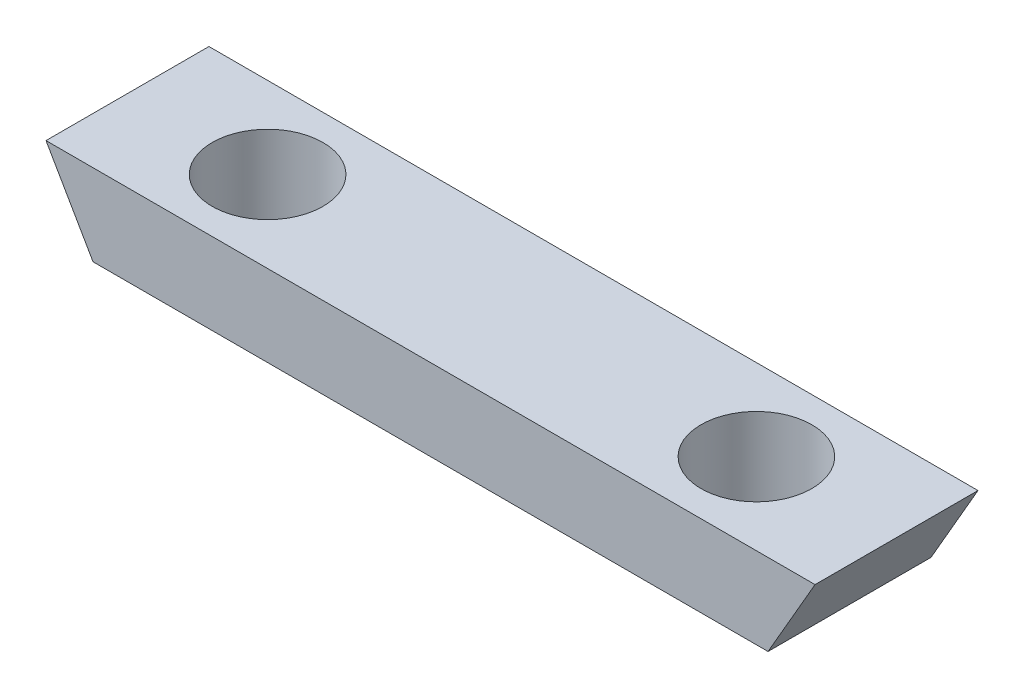
SolidWorks part; units mm, degrees
ref_plane "Front Plane" through (0, 0, 0) normal (0, 0, 1) x (1, 0, 0)
ref_plane "Top Plane" through (0, 0, 0) normal (0, 1, 0) x (1, 0, 0)
ref_plane "Right Plane" through (0, 0, 0) normal (1, 0, 0) x (0, 0, -1)
sketch "Sketch1" plane through (0, 0, 0) normal (0, 0, 1) x (1, 0, 0)
  line L0 (-14.986, 0) -> (14.986, 0)
  line L1 (-14.986, 0) -> (-13.1529, -3.175)
  line L3 (14.986, 0) -> (13.1529, -3.175)
  line L4 (-13.1529, -3.175) -> (13.1529, -3.175)
  dimension "D1" = 29.972
  dimension "D2" = 14.986
  dimension "D3" = 60
  dimension "D4" = 3.175
  dimension "D5" = 60
  dimension "D6" = 3.175
extrude "Boss-Extrude1" add sketch "Sketch1" along normal blind 6.35
sketch "Sketch2" plane through (0, -3.175, 0) normal (0, -1, 0) x (1, 0, 0)
  line L0 (-13.1529, 3.175) -> (13.1529, 3.175)
  line L1 (-13.1529, 6.35) -> (-13.1529, 0) construction
  line L2 (13.1529, 6.35) -> (13.1529, 0) construction
  line L3 (0, 6.35) -> (0, 0)
  line L4 (-13.1529, 6.35) -> (13.1529, 6.35) construction
  line L5 (-13.1529, 0) -> (13.1529, 0) construction
  circle A0 centre (-9.525, 3.175) radius 2.159
  circle A1 centre (9.525, 3.175) radius 2.159
  point P16 (0, 3.175)
  dimension "D1" = 19.05
  dimension "D2" = 9.525
extrude "Cut-Extrude1" cut sketch "Sketch2" against normal blind 5.08 contours A0 | A1
